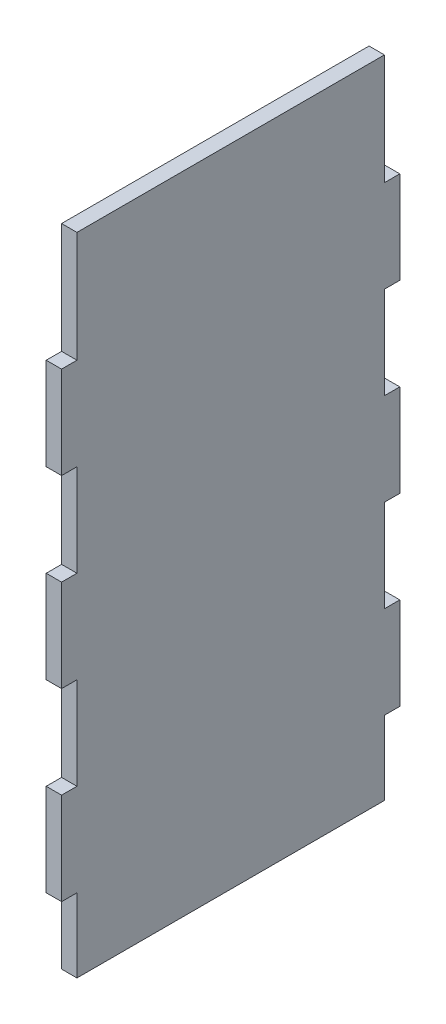
SolidWorks part; units mm, degrees
ref_plane "Front Plane" through (0, 0, 0) normal (0, 0, 1) x (1, 0, 0)
ref_plane "Top Plane" through (0, 0, 0) normal (0, 1, 0) x (1, 0, 0)
ref_plane "Right Plane" through (0, 0, 0) normal (1, 0, 0) x (0, 0, -1)
sketch "Sketch1" plane through (0, 0, 0) normal (1, 0, 0) x (0, 0, -1)
  line L0 (0, 110.49) -> (3.175, 110.49)
  line L1 (0, 0) -> (-63.5, 0)
  line L2 (0, 0) -> (0, 15.24)
  line L3 (0, 133.35) -> (-63.5, 133.35)
  line L4 (-63.5, 0) -> (-63.5, 15.24)
  line L5 (3.175, 110.49) -> (3.175, 91.44)
  line L6 (3.175, 91.44) -> (0, 91.44)
  line L7 (0, 110.49) -> (0, 133.35)
  line L8 (0, 72.39) -> (3.175, 72.39)
  line L9 (3.175, 72.39) -> (3.175, 53.34)
  line L10 (3.175, 53.34) -> (0, 53.34)
  line L11 (0, 34.29) -> (3.175, 34.29)
  line L12 (3.175, 34.29) -> (3.175, 15.24)
  line L13 (3.175, 15.24) -> (0, 15.24)
  line L14 (0, 72.39) -> (0, 91.44)
  line L15 (0, 34.29) -> (0, 53.34)
  line L16 (-31.75, 133.35) -> (-31.75, 0) construction
  line L17 (-66.675, 15.24) -> (-63.5, 15.24)
  line L18 (-63.5, 34.29) -> (-66.675, 34.29)
  line L19 (-66.675, 53.34) -> (-63.5, 53.34)
  line L20 (-66.675, 72.39) -> (-66.675, 53.34)
  line L21 (-63.5, 72.39) -> (-66.675, 72.39)
  line L22 (-66.675, 91.44) -> (-63.5, 91.44)
  line L23 (-66.675, 110.49) -> (-66.675, 91.44)
  line L24 (-63.5, 110.49) -> (-66.675, 110.49)
  line L25 (-63.5, 110.49) -> (-63.5, 133.35)
  line L26 (-63.5, 72.39) -> (-63.5, 91.44)
  line L27 (-66.675, 34.29) -> (-66.675, 15.24)
  line L28 (-63.5, 34.29) -> (-63.5, 53.34)
  dimension "D1" = 63.5
  dimension "D2" = 133.35
  dimension "D3" = 3.175
  dimension "D4" = 19.05
  dimension "D5" = 22.86
  dimension "D6" = 3
extrude "Boss-Extrude1" add sketch "Sketch1" along normal blind 3.175
